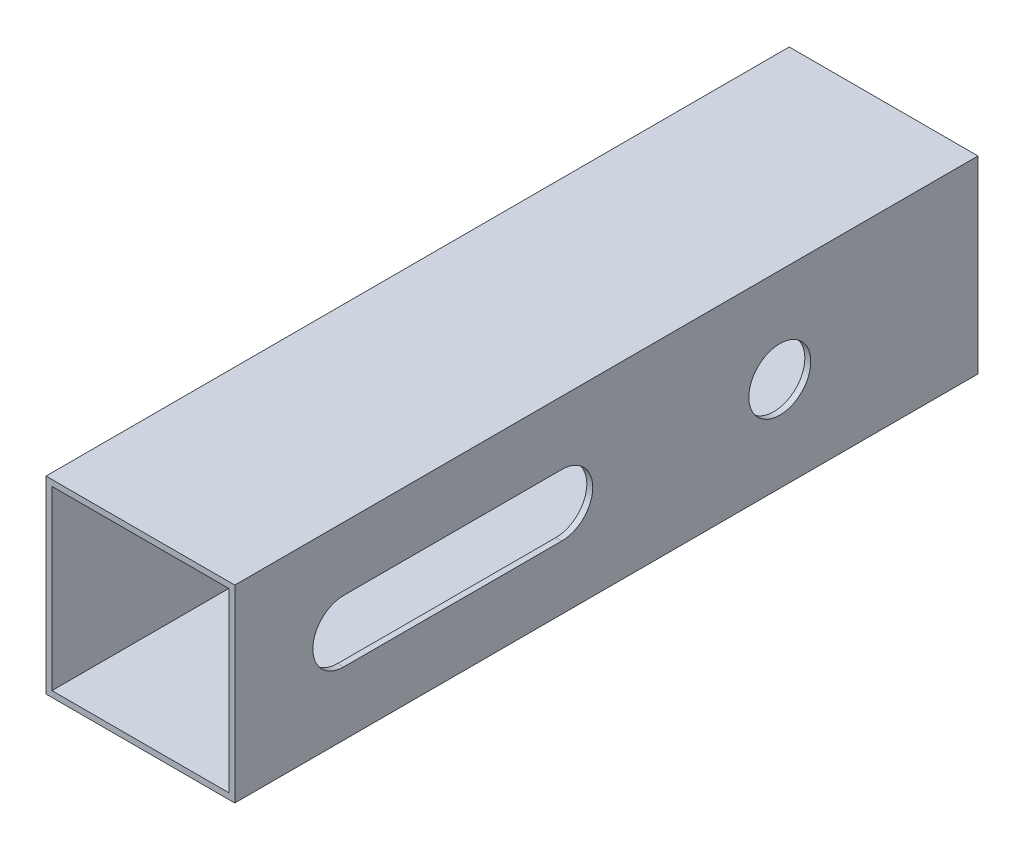
SolidWorks part; units mm, degrees
ref_plane "Alzado" through (0, 0, 0) normal (0, 0, 1) x (1, 0, 0)
ref_plane "Planta" through (0, 0, 0) normal (0, 1, 0) x (1, 0, 0)
ref_plane "Vista lateral" through (0, 0, 0) normal (1, 0, 0) x (0, 0, -1)
sketch "Croquis1" plane through (0, 0, 0) normal (0, 0, 1) x (1, 0, 0)
  line L2 (-19.05, 19.05) -> (19.05, 19.05)
  line L3 (-19.05, 19.05) -> (-19.05, -19.05)
  line L4 (-19.05, -19.05) -> (19.05, -19.05)
  line L5 (19.05, 19.05) -> (19.05, -19.05)
  line L6 (-19.05, 19.05) -> (19.05, -19.05) construction
  line L7 (-19.05, -19.05) -> (19.05, 19.05) construction
  point P2 (0, 0)
  dimension "D1" = 38.1
  dimension "D2" = 38.1
extrude "Saliente-Extruir1" add sketch "Croquis1" along normal blind 150
sketch "Croquis2" plane through (19.05, 0, 0) normal (1, 0, 0) x (0, 0, -1)
  line L2 (-128, -6.25) -> (-84, -6.25)
  line L3 (-128, 6.25) -> (-84, 6.25)
  circle A5 centre (-40, 0) radius 6.25
  arc A6 (-84, -6.25) -> (-84, 6.25) centre (-84, 0) ccw
  arc A7 (-128, 6.25) -> (-128, -6.25) centre (-128, 0) ccw
  dimension "D4" = 44
  dimension "D6" = 44
  dimension "D2" = 40
sketch "Croquis4" plane through (0, 0, 0) normal (0, 0, -1) x (-1, 0, 0)
  line L0 (-19.05, 19.05) -> (19.05, 19.05) construction
  line L1 (-17.85, 17.85) -> (17.85, 17.85)
  line L2 (-17.85, 17.85) -> (-17.85, -17.85)
  line L3 (-17.85, -17.85) -> (17.85, -17.85)
  line L4 (17.85, 17.85) -> (17.85, -17.85)
  line L5 (-17.85, 17.85) -> (17.85, -17.85) construction
  line L6 (-17.85, -17.85) -> (17.85, 17.85) construction
  line L7 (19.05, 19.05) -> (19.05, -19.05) construction
  point P0 (0, 0)
  dimension "D1" = 1.2
  dimension "D2" = 1.2
extrude "Cortar-Extruir3" cut sketch "Croquis4" against normal blind 300
extrude "Cortar-Extruir5" cut sketch "Croquis2" against normal blind 10
